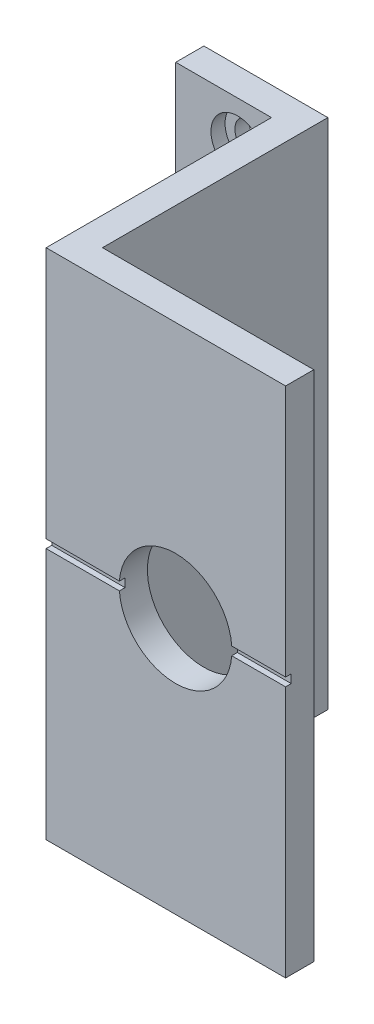
SolidWorks part; units mm, degrees
ref_plane "前基準面" through (0, 0, 0) normal (0, 0, 1) x (1, 0, 0)
ref_plane "上基準面" through (0, 0, 0) normal (0, 1, 0) x (1, 0, 0)
ref_plane "右基準面" through (0, 0, 0) normal (1, 0, 0) x (0, 0, -1)
sketch "草圖3" plane through (0, 0, 0) normal (0, 0, 1) x (1, 0, 0)
  line L1 (1.2608, 16.986) -> (5.6608, 16.986)
  line L2 (1.2608, 16.986) -> (1.2608, -1.214)
  line L3 (1.2608, -1.214) -> (5.6608, -1.214)
  line L4 (5.6608, 16.986) -> (5.6608, -1.214)
  dimension "D1" = 18.2
  dimension "D2" = 4.4
extrude "填料-伸長1" add sketch "草圖3" along normal blind 1
sketch "草圖4" plane through (0, 0, 1) normal (0, 0, 1) x (1, 0, 0)
  line L0 (3.4608, 0.286) -> (1.2608, 0.286) construction
  line L1 (1.2608, 16.986) -> (1.2608, -1.214) construction
  line L2 (3.4608, 0.286) -> (3.4608, -1.214) construction
  line L3 (1.2608, -1.214) -> (5.6608, -1.214) construction
  line L4 (3.4608, 15.486) -> (3.4608, 16.986) construction
  line L5 (5.6608, 16.986) -> (1.2608, 16.986) construction
  line L6 (3.4608, 0.286) -> (3.4608, 2.786) construction
  line L7 (3.4608, 15.486) -> (3.4608, 12.986) construction
  circle A0 centre (3.4608, 15.486) radius 0.95
  circle A1 centre (3.4608, 0.286) radius 0.95
  circle A2 centre (3.4608, 12.986) radius 0.95
  circle A3 centre (3.4608, 2.786) radius 0.95
  dimension "D3" = 1.9
  dimension "D1" = 1.5
  dimension "D2" = 2.5
  dimension "D4" = 2.2
extrude "除料-伸長1" cut sketch "草圖4" against normal blind 0.5
sketch "草圖5" plane through (0, 0, 1) normal (0, 0, 1) x (1, 0, 0)
  line L0 (5.6608, 16.986) -> (1.2608, 16.986) construction
  line L1 (4.6608, 16.986) -> (5.6608, 16.986)
  line L2 (4.6608, 16.986) -> (4.6608, -1.214)
  line L3 (4.6608, -1.214) -> (5.6608, -1.214)
  line L4 (5.6608, 16.986) -> (5.6608, -1.214)
  line L5 (1.2608, -1.214) -> (5.6608, -1.214) construction
  line L6 (5.6608, -1.214) -> (5.6608, 16.986) construction
  dimension "D1" = 1
extrude "填料-伸長2" add sketch "草圖5" along normal blind 7
sketch "草圖6" plane through (0, 0, 8) normal (0, 0, 1) x (1, 0, 0)
  line L0 (1.2608, 16.986) -> (17.2489, -1.214) construction
  line L1 (1.2608, 16.986) -> (1.2608, -1.214) construction
  line L2 (4.6608, 16.986) -> (1.2608, 16.986) construction
  line L5 (4.6608, 16.986) -> (4.6608, -1.214) construction
  line L6 (4.6608, 16.986) -> (13.1608, 16.986)
  line L7 (4.6608, 16.986) -> (4.6608, -1.214)
  line L8 (4.6608, -1.214) -> (13.1608, -1.214)
  line L9 (13.1608, 16.986) -> (13.1608, -1.214)
  circle A0 centre (9.2548, 7.886) radius 2
  dimension "D4" = 4
  dimension "D1" = 8.5
  dimension "D3" = 9.1
  dimension "D5" = 18.2
extrude "填料-伸長3" add sketch "草圖6" along normal blind 1
sketch "草圖8" plane through (0, 0, 9) normal (0, 0, 1) x (1, 0, 0)
  line L0 (4.6608, 16.986) -> (4.6608, -1.214) construction
  line L1 (4.6608, 8.036) -> (13.1608, 8.036)
  line L2 (4.6608, 8.036) -> (4.6608, 7.736)
  line L3 (4.6608, 7.736) -> (13.1608, 7.736)
  line L4 (13.1608, 8.036) -> (13.1608, 7.736)
  line L5 (13.1608, -1.214) -> (13.1608, 16.986) construction
  point P8 (13.1608, 7.886)
  point P9 (13.1608, 7.886)
  dimension "D1" = 0.3
extrude "除料-伸長3" cut sketch "草圖8" against normal blind 0.2
sketch "草圖9" plane through (0, 0, 0.5) normal (0, 0, 1) x (1, 0, 0)
  circle A0 centre (3.4608, 15.486) radius 0.6
  circle A1 centre (3.4608, 12.986) radius 0.6
  circle A2 centre (3.4608, 2.786) radius 0.6
  circle A3 centre (3.4608, 0.286) radius 0.6
  dimension "D1" = 1.2
extrude "除料-伸長4" cut sketch "草圖9" against normal through all
sketch "草圖10" plane through (1.2608, 0, 0) normal (-1, 0, 0) x (0, 0, 1)
  line L0 (1, 16.986) -> (1, -1.214) construction
  line L3 (0, 10.536) -> (1, 10.536)
  line L6 (1, 5.236) -> (0, 5.236)
  line L12 (0, 10.536) -> (0, 5.236)
  line L13 (1, 10.536) -> (1, 5.236)
  dimension "D1" = 6.45
  dimension "D2" = 1
  dimension "D3" = 5.3
extrude "除料-伸長5" cut sketch "草圖10" against normal blind 2
fillet "圓角1" radius 0.5 2 edges at (3.2608, 5.236, 0.5) (3.2608, 10.536, 0.5)
